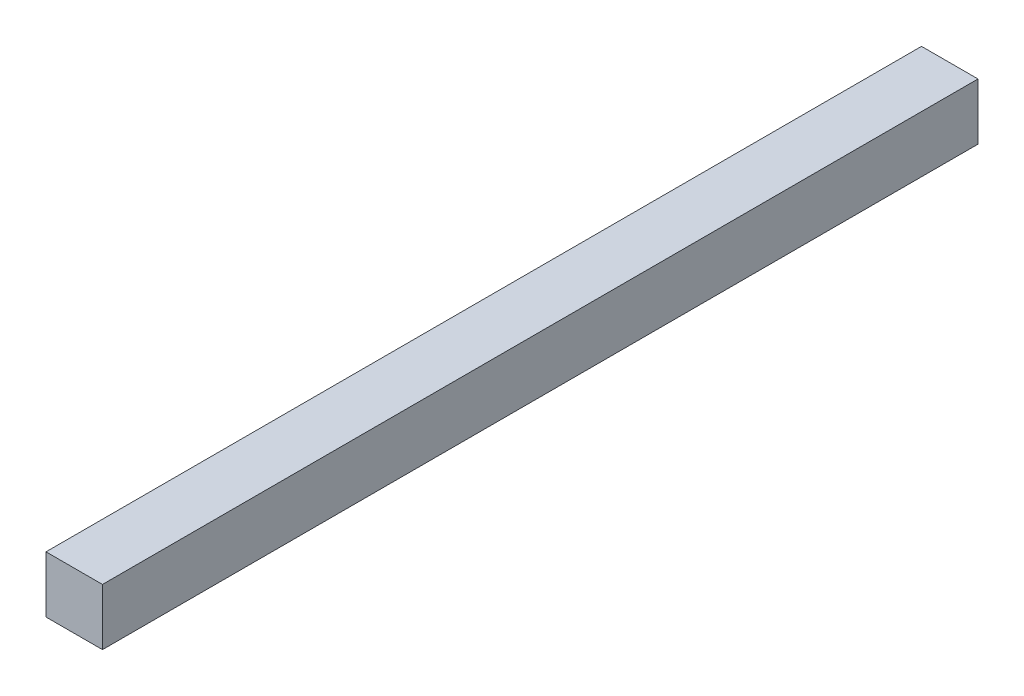
SolidWorks part; units mm, degrees
ref_plane "Front" through (0, 0, 0) normal (0, 0, 1) x (1, 0, 0)
ref_plane "Top" through (0, 0, 0) normal (0, 1, 0) x (1, 0, 0)
ref_plane "Right" through (0, 0, 0) normal (1, 0, 0) x (0, 0, -1)
sketch "Sketch1" plane through (0, 0, 0) normal (0, 0, 1) x (1, 0, 0)
  line L1 (-10, 10) -> (10, 10)
  line L2 (-10, 10) -> (-10, -10)
  line L3 (-10, -10) -> (10, -10)
  line L4 (10, 10) -> (10, -10)
  dimension "D1" = 20
  dimension "D2" = 20
  dimension "D3" = 10
  dimension "D4" = 10
extrude "Boss-Extrude1" add sketch "Sketch1" along normal blind 310
